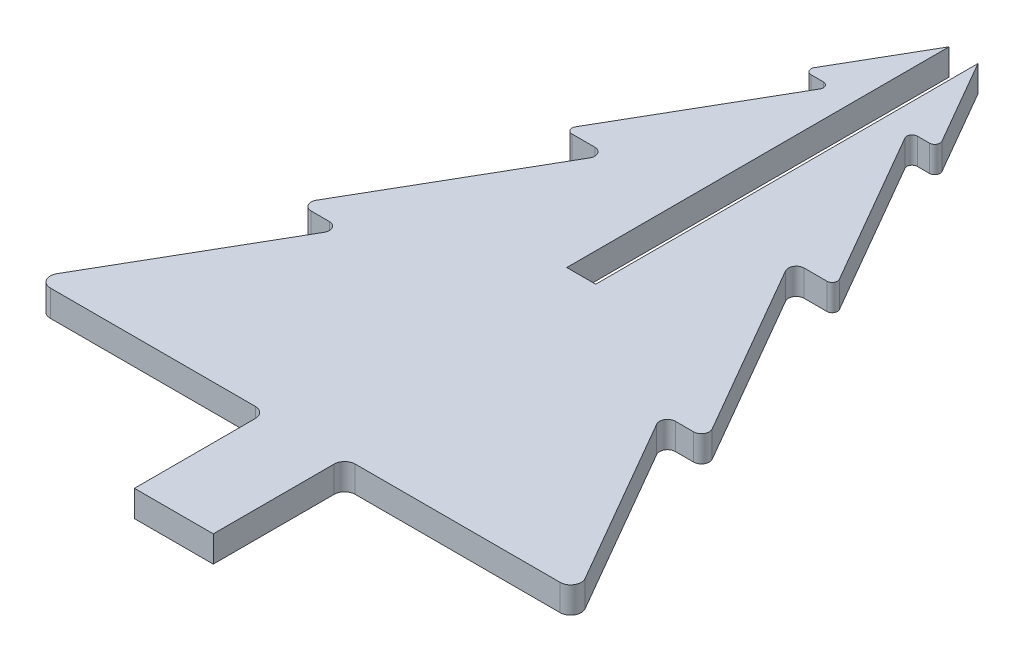
SolidWorks part; units mm, degrees
ref_plane "Plano frontal" through (0, 0, 0) normal (0, 0, 1) x (1, 0, 0)
ref_plane "Plano superior" through (0, 0, 0) normal (0, 1, 0) x (1, 0, 0)
ref_plane "Plano direito" through (0, 0, 0) normal (1, 0, 0) x (0, 0, -1)
sketch "Esboço1" plane through (0, 0, 0) normal (0, 1, 0) x (1, 0, 0)
  line L0 (0, 16.1772) -> (0, -226.058) construction
  line L1 (-7.5, -140) -> (7.5, -140)
  line L2 (0, -25) -> (-51.9615, -115)
  line L3 (-51.9615, -115) -> (51.9615, -115)
  line L4 (51.9615, -115) -> (0, -25)
  line L5 (0, 15) -> (-12.9904, -7.5)
  line L6 (-12.9904, -7.5) -> (12.9904, -7.5)
  line L7 (12.9904, -7.5) -> (0, 15)
  line L8 (0, 5) -> (-25.9808, -40)
  line L9 (-25.9808, -40) -> (25.9808, -40)
  line L10 (25.9808, -40) -> (0, 5)
  line L11 (0, -10) -> (-38.9711, -77.5)
  line L12 (-38.9711, -77.5) -> (38.9711, -77.5)
  line L13 (38.9711, -77.5) -> (0, -10)
  line L14 (-7.5, -140) -> (-7.5, -115)
  line L15 (7.5, -140) -> (7.5, -115)
  circle A0 centre (0, 0) radius 7.5 construction
  circle A1 centre (0, -25) radius 15 construction
  circle A2 centre (0, -55) radius 22.5 construction
  circle A3 centre (0, -85) radius 30 construction
  point P6 (0, 0)
  point P9 (0, -10)
  point P28 (0, -140)
  dimension "D2" = 15
  dimension "D6" = 30
  dimension "D9" = 45
  dimension "D11" = 60
  dimension "D1" = 0
  dimension "D3" = 25
  dimension "D4" = 90
  dimension "D5" = 90
  dimension "D7" = 30
  dimension "D8" = 90
  dimension "D10" = 90
  dimension "D12" = 30
  dimension "D13" = 15
  dimension "D14" = 55
extrude "Árvore" add sketch "Esboço1" along normal blind 5 contours L1 L15 L3 L14 | L12 L2 L3 L4 | L2 L12 L4 L9 | L9 L13 L11 L2 L4 | L12 L13 L9 L4 | L2 L9 L4 | L11 L12 L2 L9 | L13 L9 L10 L6 L8 L11 | L6 L10 L8 | L10 L6 L7 L5 L8
sketch "Esboço3" plane through (0, 5, 0) normal (0, 1, 0) x (1, 0, 0)
  line L0 (0, 19.2247) -> (0, -147.1319) construction
  line L2 (-2.75, -62.5) -> (2.75, -62.5)
  line L3 (-2.75, -62.5) -> (-2.75, 15)
  line L4 (-2.75, 15) -> (2.75, 15)
  line L5 (2.75, -62.5) -> (2.75, 15)
  line L6 (-2.75, -62.5) -> (2.75, 15) construction
  line L7 (-2.75, 15) -> (2.75, -62.5) construction
  point P3 (0, -23.75)
  dimension "D1" = 5.5
  dimension "D2" = 77.5
  dimension "D3" = 0
extrude "Encaixe" cut sketch "Esboço3" against normal blind 5
fillet "Filete1" radius 1.5 1 edges at (17.3205, 2.5, 40)
fillet "Filete2" radius 1 1 edges at (25.9808, 2.5, 40)
fillet "Filete3" radius 1.5 1 edges at (38.9711, 2.5, 77.5)
fillet "Filete4" radius 1.5 1 edges at (30.3109, 2.5, 77.5)
fillet "Filete5" radius 2 1 edges at (51.9615, 2.5, 115)
fillet "Filete6" radius 1 1 edges at (12.9904, 2.5, 7.5)
fillet "Filete7" radius 1 1 edges at (7.2169, 2.5, 7.5)
fillet "Filete8" radius 2 1 edges at (-51.9615, 2.5, 115)
fillet "Filete9" radius 1.5 1 edges at (-30.3109, 2.5, 77.5)
fillet "Filete10" radius 1.5 1 edges at (-38.9711, 2.5, 77.5)
fillet "Filete11" radius 1.5 1 edges at (-17.3205, 2.5, 40)
fillet "Filete12" radius 1 1 edges at (-25.9808, 2.5, 40)
fillet "Filete13" radius 1 1 edges at (-7.2169, 2.5, 7.5)
fillet "Filete14" radius 1 1 edges at (-12.9904, 2.5, 7.5)
fillet "Filete15" radius 2 1 edges at (-7.5, 2.5, 115)
fillet "Filete16" radius 2 1 edges at (7.5, 2.5, 115)
